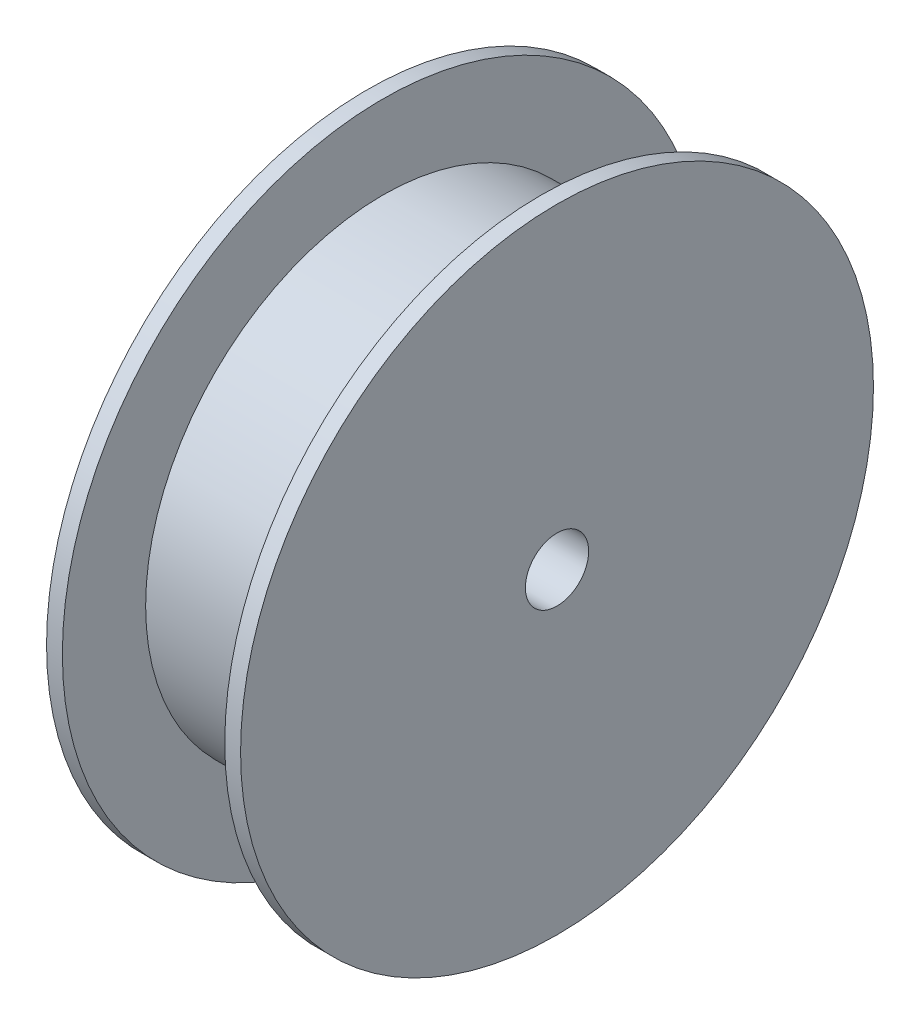
SolidWorks part; units mm, degrees
ref_plane "Plan de face" through (0, 0, 0) normal (0, 0, 1) x (1, 0, 0)
ref_plane "Plan de dessus" through (0, 0, 0) normal (0, 1, 0) x (1, 0, 0)
ref_plane "Plan de droite" through (0, 0, 0) normal (1, 0, 0) x (0, 0, -1)
sketch "Esquisse1" plane through (0, 0, 0) normal (0, 0, 1) x (1, 0, 0)
  line L0 (0, 0) -> (5.5, 0)
  line L1 (5.5, 0) -> (5.5, 20)
  line L2 (5.5, 20) -> (4.5, 20)
  line L3 (4.5, 20) -> (4.5, 15)
  line L4 (4.5, 15) -> (-5.5, 15)
  line L5 (-5.5, 15) -> (-5.5, 20.2632)
  line L6 (-5.5, 20.2632) -> (-6.5, 20.2632)
  line L7 (-6.5, 20.2632) -> (-6.5, 0)
  line L8 (-6.5, 0) -> (0, 0)
  dimension "D1" = 10
  dimension "D2" = 1
  dimension "D3" = 1
  dimension "D4" = 5.5
  dimension "D5" = 20
  dimension "D6" = 5
revolve "Révolution1" add sketch "Esquisse1" angle 360 about L8
sketch "Esquisse2" plane through (5.5, 0, 0) normal (1, 0, 0) x (0, 0, -1)
  circle A0 centre (0, 0) radius 2
  dimension "D1" = 4
extrude "Enlèv. mat.-Extru.1" cut sketch "Esquisse2" against normal through all
